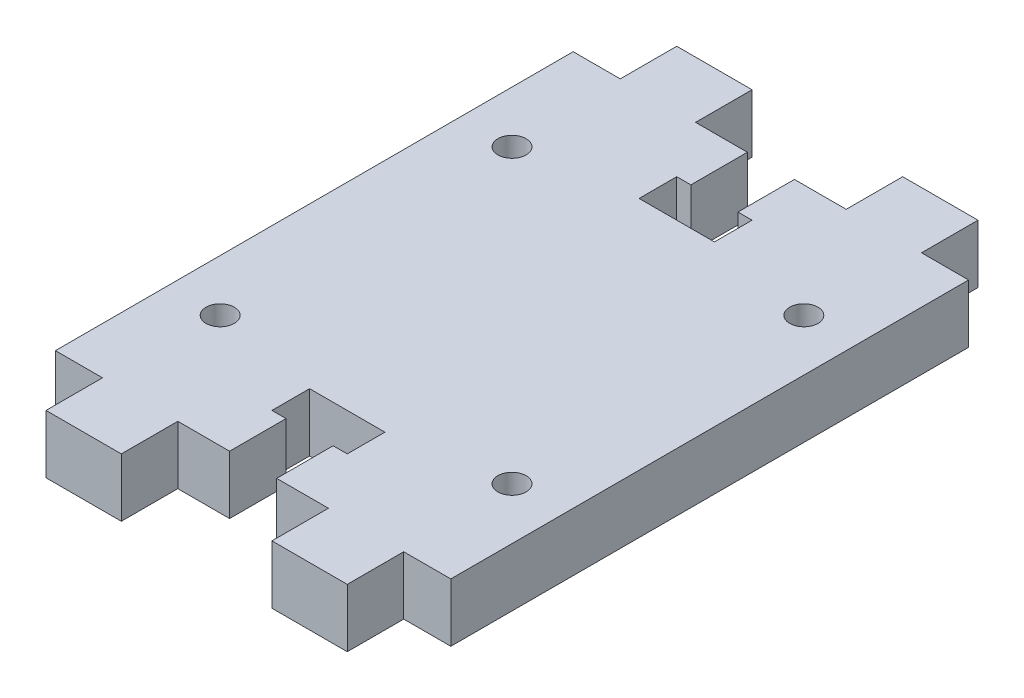
SolidWorks part; units mm, degrees
ref_plane "Front Plane" through (0, 0, 0) normal (0, 0, 1) x (1, 0, 0)
ref_plane "Top Plane" through (0, 0, 0) normal (0, 1, 0) x (1, 0, 0)
ref_plane "Right Plane" through (0, 0, 0) normal (1, 0, 0) x (0, 0, -1)
sketch "Sketch1" plane through (0, 0, 0) normal (0, 1, 0) x (1, 0, 0)
  line L0 (-21, 0) -> (21, 0) construction
  line L1 (-21, 27.5) -> (-16, 27.5)
  line L2 (-21, 27.5) -> (-21, -27.5)
  line L3 (-21, -27.5) -> (-16, -27.5)
  line L4 (21, 27.5) -> (21, -27.5)
  line L5 (-21, 27.5) -> (21, -27.5) construction
  line L6 (-21, -27.5) -> (21, 27.5) construction
  line L8 (8, 27.5) -> (8, 33.5)
  line L9 (8, 33.5) -> (16, 33.5)
  line L10 (16, 27.5) -> (16, 33.5)
  line L11 (16, -27.5) -> (16, -33.5)
  line L12 (8, -33.5) -> (16, -33.5)
  line L13 (8, -27.5) -> (8, -33.5)
  line L14 (16, 27.5) -> (21, 27.5)
  line L15 (16, -27.5) -> (21, -27.5)
  line L16 (0, 0) -> (0, 27.5) construction
  line L17 (-8, -27.5) -> (-8, -33.5)
  line L18 (-8, -33.5) -> (-16, -33.5)
  line L19 (-16, -27.5) -> (-16, -33.5)
  line L20 (-16, 27.5) -> (-16, 33.5)
  line L21 (-8, 33.5) -> (-16, 33.5)
  line L22 (-8, 27.5) -> (-8, 33.5)
  line L23 (-8, 27.5) -> (-2.5, 27.5)
  line L24 (-8, -27.5) -> (-2.5, -27.5)
  line L25 (2.5, 21.5) -> (4, 21.5)
  line L26 (-4, 21.5) -> (-2.5, 21.5)
  line L27 (-4, 21.5) -> (-4, 17.5)
  line L28 (-4, 17.5) -> (4, 17.5)
  line L29 (4, 21.5) -> (4, 17.5)
  line L31 (-2.5, 27.5) -> (-2.5, 21.5)
  line L33 (2.5, 27.5) -> (2.5, 21.5)
  line L34 (2.5, 27.5) -> (8, 27.5)
  line L35 (2.5, -27.5) -> (2.5, -21.5)
  line L36 (-2.5, -27.5) -> (-2.5, -21.5)
  line L37 (4, -21.5) -> (4, -17.5)
  line L38 (-4, -17.5) -> (4, -17.5)
  line L39 (-4, -21.5) -> (-4, -17.5)
  line L40 (-4, -21.5) -> (-2.5, -21.5)
  line L41 (2.5, -21.5) -> (4, -21.5)
  line L42 (2.5, -27.5) -> (8, -27.5)
  point P0 (0, 0)
  dimension "D1" = 42
  dimension "D2" = 55
  dimension "D3" = 6
  dimension "D4" = 8
  dimension "D5" = 5
  dimension "D6" = 8
  dimension "D7" = 4
  dimension "D8" = 6
  dimension "D9" = 5
  dimension "D10" = 2.5
  dimension "D11" = 4
extrude "Boss-Extrude1" add sketch "Sketch1" along normal blind 6.2
sketch "Sketch2" plane through (0, 6.2, 0) normal (0, 1, 0) x (1, 0, 0)
  circle A0 centre (15.5, -15.5) radius 1.5 construction
  circle A1 centre (-15.5, -15.5) radius 1.5 construction
  circle A2 centre (-15.5, 15.5) radius 1.5 construction
  circle A3 centre (15.5, 15.5) radius 1.5 construction
  circle A4 centre (15.5, -15.5) radius 1.5
  circle A5 centre (-15.5, -15.5) radius 1.5
  circle A6 centre (-15.5, 15.5) radius 1.5
  circle A7 centre (15.5, 15.5) radius 1.5
extrude "Cut-Extrude1" cut sketch "Sketch2" against normal up to next
